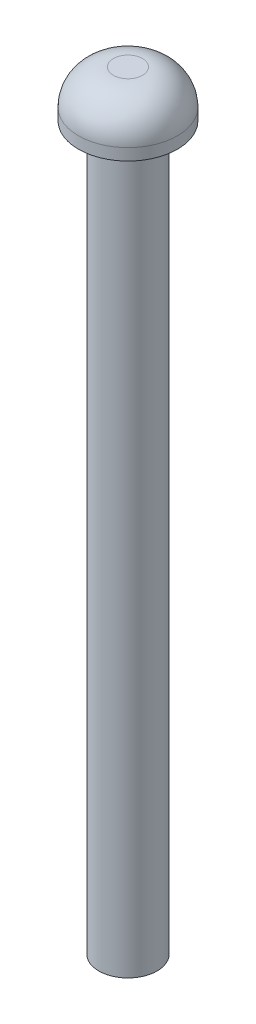
SolidWorks part; units mm, degrees
ref_plane "Alzado" through (0, 0, 0) normal (0, 0, 1) x (1, 0, 0)
ref_plane "Planta" through (0, 0, 0) normal (0, 1, 0) x (1, 0, 0)
ref_plane "Vista lateral" through (0, 0, 0) normal (1, 0, 0) x (0, 0, -1)
sketch "Croquis1" plane through (0, 0, 0) normal (0, 1, 0) x (1, 0, 0)
  circle A0 centre (0, 0) radius 2.5
  dimension "D1" = 5
extrude "Saliente-Extruir1" add sketch "Croquis1" along normal blind 62
sketch "Croquis2" plane through (0, 62, 0) normal (0, 1, 0) x (1, 0, 0)
  circle A0 centre (0, 0) radius 4.25
  dimension "D1" = 8.5
extrude "Saliente-Extruir2" add sketch "Croquis2" along normal blind 4
fillet "Redondeo1" radius 3 1 edges at (0, 66, 4.25)
